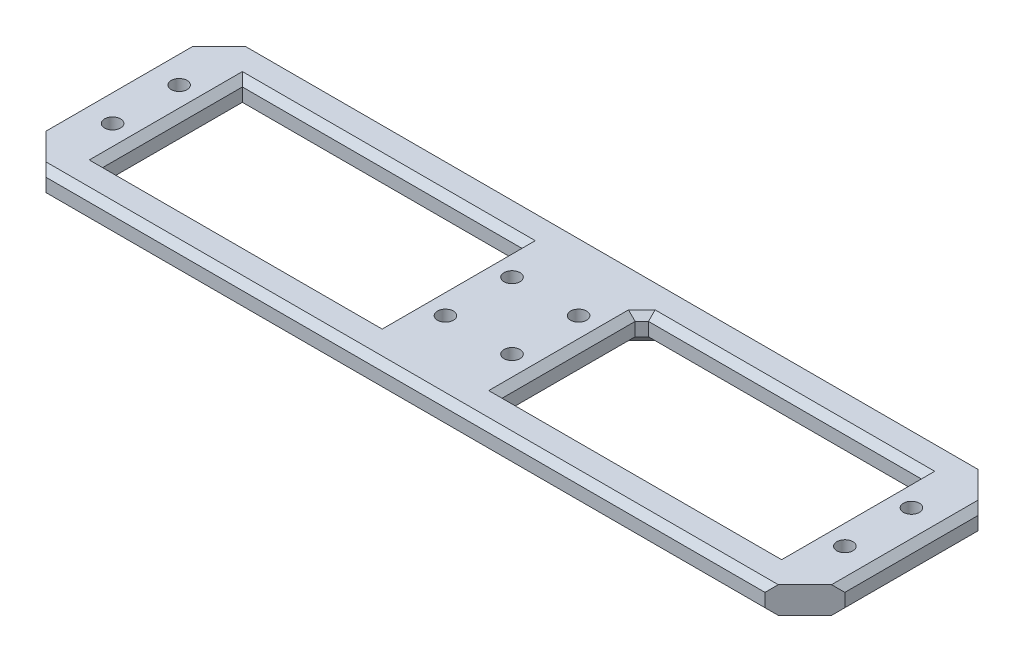
SolidWorks part; units mm, degrees
material "ABS"
ref_plane "Front Plane" through (0, 0, 0) normal (0, 0, 1) x (1, 0, 0)
ref_plane "Top Plane" through (0, 0, 0) normal (0, 1, 0) x (1, 0, 0)
ref_plane "Right Plane" through (0, 0, 0) normal (1, 0, 0) x (0, 0, -1)
sketch "Sketch1" plane through (0, 0, 0) normal (0, 1, 0) x (1, 0, 0)
  line L1 (-60, 16) -> (60, 16)
  line L2 (-60, 16) -> (-60, -16)
  line L3 (-60, -16) -> (60, -16)
  line L4 (60, 16) -> (60, -16)
  line L5 (-60, 16) -> (60, -16) construction
  line L6 (-60, -16) -> (60, 16) construction
  point P0 (0, 0)
  dimension "D1" = 120
  dimension "D2" = 32
extrude "Boss-Extrude1" add sketch "Sketch1" along normal blind 4
sketch "Sketch2" plane through (0, 4, 0) normal (0, 1, 0) x (1, 0, 0)
  line L0 (-60, -16) -> (60, -16) construction
  line L1 (9, -10.5) -> (51, -10.5)
  line L2 (9, -10.5) -> (9, 10.5)
  line L3 (9, 10.5) -> (51, 10.5)
  line L4 (51, -10.5) -> (51, 10.5)
  circle A0 centre (55, 5) radius 1.2
  circle A1 centre (55, -5) radius 1.2
  circle A2 centre (5, 5) radius 1.2
  circle A3 centre (5, -5) radius 1.2
  dimension "D6" = 2.4
  dimension "D1" = 42
  dimension "D2" = 21
  dimension "D3" = 5.5
  dimension "D4" = 9
  dimension "D5" = 4
  dimension "D7" = 10
  dimension "D8" = 5.5
  dimension "D9" = 4
extrude "Cut-Extrude1" cut sketch "Sketch2" against normal blind 4
ref_plane "Plane1" through (0, 0, 0) normal (1, 0, 0) x (0, 0, -1)
mirror "Mirror1" about plane through (0, 0, 0) normal (1, 0, 0) of "Cut-Extrude1"
chamfer "Chamfer1" distance 1 angle 45 28 edges at (-51, 0, 0) (-30, 0, 10.5) (-30, 0, -10.5) (-9, 0, 0) (60, 0, 0) (-60, 2, -16) (0, 0, -16) (0, 0, 16) (-60, 2, 16) (60, 2, -16) (60, 2, 16) (-60, 4, 0) (0, 4, -16) (60, 4, 0) (0, 4, 16) (-51, 4, 0) (-30, 4, -10.5) (-9, 4, 0) (-30, 4, 10.5) (30, 0, 10.5) (9, 0, 0) (51, 0, 0) (30, 0, -10.5) (9, 2, -10.5) (30, 4, 10.5) (51, 4, 0) (9, 4, 0) (30, 4, -10.5)
sketch "Sketch3" plane through (0, 0, 0) normal (0, -1, 0) x (1, 0, 0)
  line L0 (-60, 10) -> (-54, 16)
  line L1 (-60, -15) -> (-60, 15) construction
  line L2 (-59, 16) -> (59, 16) construction
  line L3 (-54, 16) -> (-63.1647, 19.3188)
  line L4 (-63.1647, 19.3188) -> (-60, 10)
  line L5 (-60, -10) -> (-54, -16)
  line L6 (59, -16) -> (-59, -16) construction
  line L7 (-54, -16) -> (-62.5539, -17.9352)
  line L8 (-62.5539, -17.9352) -> (-60, -10)
  dimension "D1" = 5
  dimension "D2" = 5
  dimension "D3" = 5
  dimension "D4" = 5
extrude "Cut-Extrude2" cut sketch "Sketch3" against normal blind 10
mirror "Mirror2" about plane through (0, 0, 0) normal (1, 0, 0) of "Cut-Extrude2"
